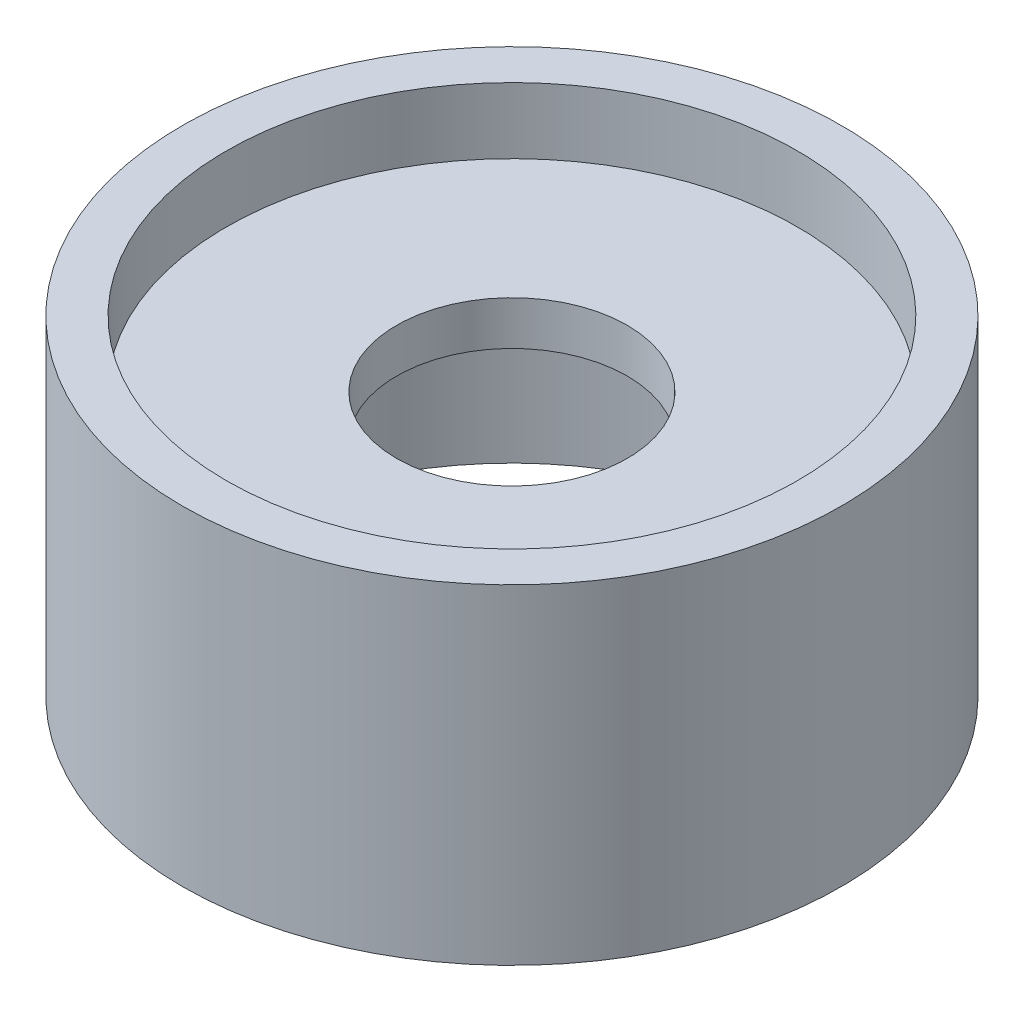
SolidWorks part; units mm, degrees
ref_plane "Front Plane" through (0, 0, 0) normal (0, 0, 1) x (1, 0, 0)
ref_plane "Top Plane" through (0, 0, 0) normal (0, 1, 0) x (1, 0, 0)
ref_plane "Right Plane" through (0, 0, 0) normal (1, 0, 0) x (0, 0, -1)
sketch "Sketch1" plane through (0, 0, 0) normal (0, 1, 0) x (1, 0, 0)
  circle A0 centre (0, 0) radius 13
  circle A1 centre (0, 0) radius 15
extrude "Boss-Extrude1" add sketch "Sketch1" along normal blind 5 and the other way blind 10
sketch "Sketch2" plane through (0, 0, 0) normal (0, 1, 0) x (1, 0, 0)
  circle A0 centre (0, 0) radius 15
extrude "Boss-Extrude2" add sketch "Sketch2" along normal blind 2
sketch "Sketch3" plane through (0, 0, 0) normal (0, 1, 0) x (1, 0, 0)
  circle A0 centre (0, 0) radius 5.25
extrude "Cut-Extrude1" cut sketch "Sketch3" against normal through all both and the other way through all
